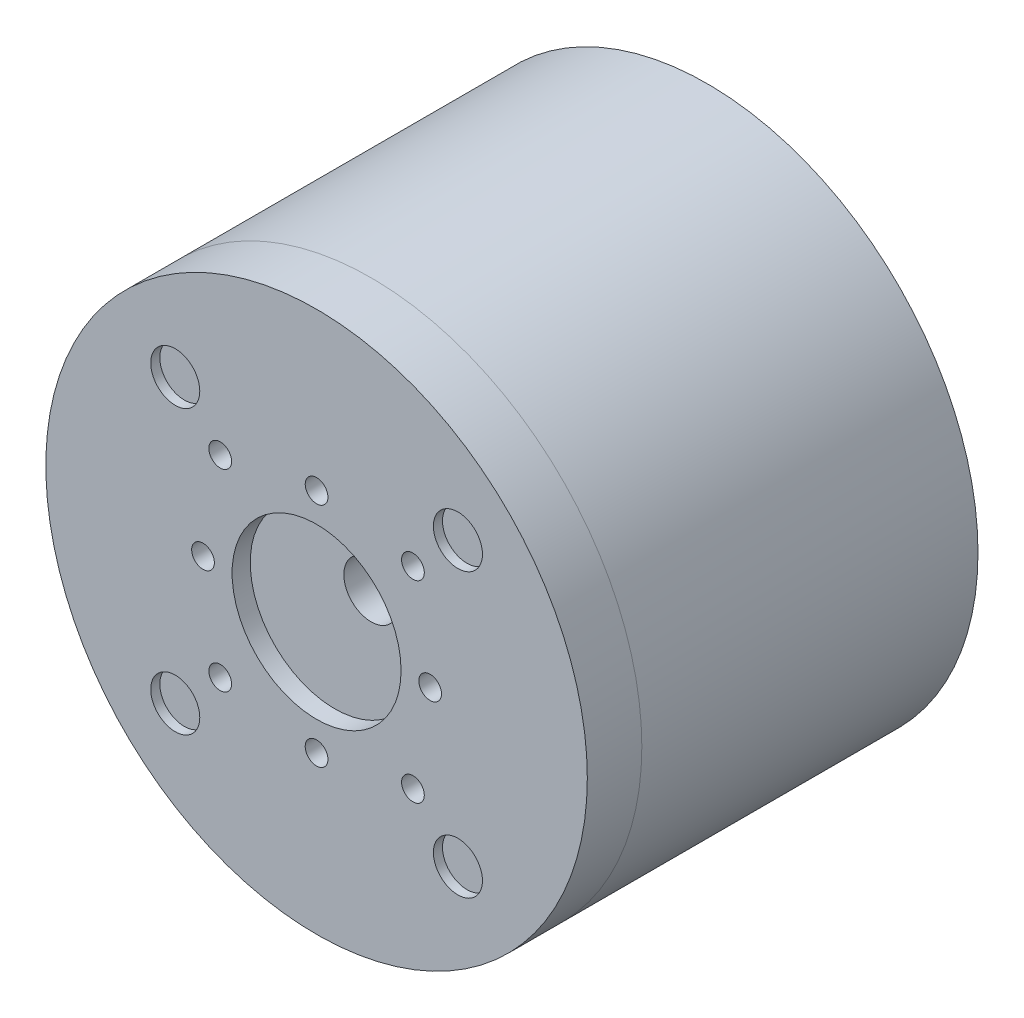
SolidWorks part; units mm, degrees
ref_plane "前视基准面" through (0, 0, 0) normal (0, 0, 1) x (1, 0, 0)
ref_plane "上视基准面" through (0, 0, 0) normal (0, 1, 0) x (1, 0, 0)
ref_plane "右视基准面" through (0, 0, 0) normal (1, 0, 0) x (0, 0, -1)
other "Configuration Table"
sketch "草图1" plane through (0, 0, 0) normal (0, 0, 1) x (1, 0, 0)
  circle A0 centre (0, 0) radius 29.8
  circle A1 centre (0, 0) radius 3
extrude "01_MainHousing_OD59.6_L37" add sketch "草图1" along normal blind 37
sketch "草图2" plane through (0, 0, 0) normal (0, 0, 1) x (1, 0, 0)
  circle A0 centre (0, 0) radius 6.35
extrude "02_FrontBearingSeat_D12.7_Depth1_ASSUMED" cut sketch "草图2" along normal blind 1
sketch "Rotor_front_PCD25_clocked45_relative_to_stator" plane through (0, 0, 0) normal (0, 0, 1) x (1, 0, 0)
  circle A0 centre (8.8388, 8.8388) radius 1.25
  circle A1 centre (-8.8388, 8.8388) radius 1.25
  circle A2 centre (-8.8388, -8.8388) radius 1.25
  circle A3 centre (8.8388, -8.8388) radius 1.25
extrude "03_Front_4xM3_PCD25_Depth5_ASSUMED" cut sketch "Rotor_front_PCD25_clocked45_relative_to_stator" along normal blind 5
sketch "草图4" plane through (0, 0, 0) normal (0, 0, 1) x (1, 0, 0)
  circle A0 centre (0, 0) radius 29.8
  circle A1 centre (0, 0) radius 27.8
extrude "04_EncoderCover_Rim_L6_ASSUMED" add sketch "草图4" along normal blind 6 from offset 37 separate body
sketch "草图5" plane through (0, 0, 0) normal (0, 0, 1) x (1, 0, 0)
  circle A0 centre (0, 0) radius 27.8
  circle A1 centre (0, 0) radius 9.3
extrude "05_EncoderCover_Face_T2_ASSUMED" add sketch "草图5" along normal blind 2 from offset 41
sketch "草图6" plane through (0, 0, 0) normal (0, 0, 1) x (1, 0, 0)
  circle A0 centre (12.5, 0) radius 1.25
  circle A1 centre (0, 12.5) radius 1.25
  circle A2 centre (-12.5, 0) radius 1.25
  circle A3 centre (0, -12.5) radius 1.25
extrude "06_Cover_4xM3_PCD25_ASSUMED" cut sketch "草图6" along normal blind 2 from offset 41
sketch "草图7" plane through (0, 0, 0) normal (0, 0, 1) x (1, 0, 0)
  circle A0 centre (10.6066, 10.6066) radius 1.25
  circle A1 centre (-10.6066, 10.6066) radius 1.25
  circle A2 centre (-10.6066, -10.6066) radius 1.25
  circle A3 centre (10.6066, -10.6066) radius 1.25
extrude "07_Cover_4xM3_PCD30_ASSUMED" cut sketch "草图7" along normal blind 2 from offset 41
sketch "草图8" plane through (0, 0, 0) normal (0, 0, 1) x (1, 0, 0)
  circle A0 centre (15.5563, 15.5563) radius 2.7
  circle A1 centre (-15.5563, 15.5563) radius 2.7
  circle A2 centre (-15.5563, -15.5563) radius 2.7
  circle A3 centre (15.5563, -15.5563) radius 2.7
extrude "08_Cover_4xFastenerSeats_PCD44_ASSUMED" cut sketch "草图8" along normal blind 1 from offset 42
